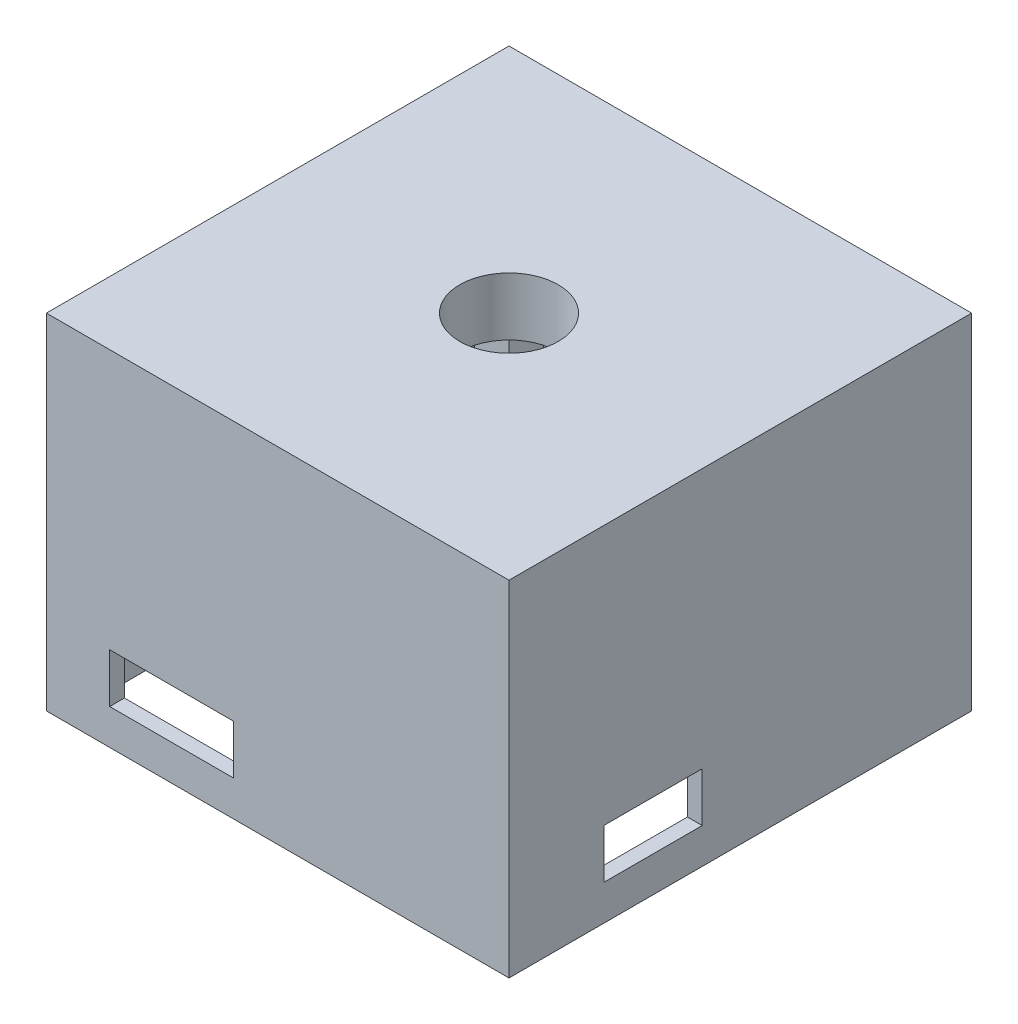
SolidWorks part; units mm, degrees
ref_plane "Front Plane" through (0, 0, 0) normal (0, 0, 1) x (1, 0, 0)
ref_plane "Top Plane" through (0, 0, 0) normal (0, 1, 0) x (1, 0, 0)
ref_plane "Right Plane" through (0, 0, 0) normal (1, 0, 0) x (0, 0, -1)
sketch "Sketch1" plane through (0, 0, 0) normal (0, 1, 0) x (1, 0, 0)
  line L1 (-23.5, -23.5) -> (23.5, -23.5)
  line L2 (-23.5, -23.5) -> (-23.5, 23.5)
  line L3 (-23.5, 23.5) -> (23.5, 23.5)
  line L4 (23.5, -23.5) -> (23.5, 23.5)
  line L5 (-23.5, -23.5) -> (23.5, 23.5) construction
  line L6 (-23.5, 23.5) -> (23.5, -23.5) construction
  point P0 (0, 0)
  dimension "D1" = 47
  dimension "D2" = 47
extrude "Boss-Extrude1" add sketch "Sketch1" along normal blind 32
sketch "Sketch2" plane through (0, 0, 0) normal (0, -1, 0) x (1, 0, 0)
  line L1 (-22, -22) -> (22, -22)
  line L2 (-22, -22) -> (-22, 22)
  line L3 (-22, 22) -> (22, 22)
  line L4 (22, -22) -> (22, 22)
  line L5 (-22, -22) -> (22, 22) construction
  line L6 (-22, 22) -> (22, -22) construction
  point P0 (0, 0)
  dimension "D1" = 44
  dimension "D2" = 44
extrude "Cut-Extrude1" cut sketch "Sketch2" against normal blind 26.1
sketch "Sketch3" plane through (0, 26.1, 0) normal (0, -1, 0) x (1, 0, 0)
  line L0 (-22, 18.5) -> (-18.5, 18.5)
  line L1 (-22, 22) -> (-18.5, 22) construction
  line L2 (-22, 22) -> (-22, 18.5) construction
  line L6 (-18.5, 18.5) -> (-18.5, 22)
  dimension "D1" = 3.5
  dimension "D2" = 3.5
extrude "Boss-Extrude2" add sketch "Sketch3" along normal blind 20.5
mirror "Mirror1" about plane through (0, 0, 0) normal (1, 0, 0) of "Boss-Extrude2" second plane through (0, 0, 0) second plane normal (0, 0, 1)
sketch "Sketch4" plane through (0, 0, -23.5) normal (0, 0, -1) x (-1, 0, 0)
  line L0 (0, 32) -> (0, 0) construction
  line L1 (-23.5, 32) -> (23.5, 32) construction
  line L121 (15, 3.1573) -> (15, 23.1573)
  line L125 (-15, 3.1573) -> (-15, 23.1573)
  line L126 (-15, 13.1573) -> (-11, 13.1573) construction
  line L132 (-13, 3.1573) -> (-11, 3.1573)
  line L135 (-13, 23.1573) -> (-11, 23.1573)
  line L136 (-13, 23.1573) -> (-13, 3.1573)
  line L137 (-13, 3.1573) -> (-11, 3.1573)
  line L138 (-11, 23.1573) -> (-11, 3.1573)
  point P5 (0, 13.1573)
  dimension "D1" = 30
  dimension "D2" = 20
extrude "Cut-Extrude3" cut sketch "Sketch4" against normal up to next contours L138 L135 L136 L132
pattern_linear "LPattern1" count 7 spacing 4 along (-1, 0, 0) of "Cut-Extrude3"
sketch "Sketch8" plane through (0, 0, -23.5) normal (0, 0, -1) x (-1, 0, 0)
  line L2 (-13, 23.1573) -> (-13, 3.1573) construction
  line L3 (-13, 21.1573) -> (13, 21.1573)
  line L4 (-13, 21.1573) -> (-13, 19.1573)
  line L6 (13, 21.1573) -> (13, 19.1573)
  line L7 (13, 23.1573) -> (13, 3.1573) construction
  line L8 (-13, 19.1573) -> (13, 19.1573)
  dimension "D1" = 2
extrude "Boss-Extrude4" add sketch "Sketch8" against normal up to vertex
pattern_linear "LPattern2" count 5 spacing 4 along (0, -1, 0) of "Boss-Extrude4"
sketch "Sketch6" plane through (0, 0, 0) normal (0, -1, 0) x (1, 0, 0)
  line L0 (-23.5, 23.5) -> (-23.5, -23.5)
  line L1 (-23.5, -23.5) -> (23.5, -23.5)
  line L2 (23.5, -23.5) -> (23.5, 23.5)
  line L3 (23.5, 23.5) -> (-23.5, 23.5)
  line L9 (-22, 22) -> (22, 22)
  line L10 (-22, 22) -> (-22, -22)
  line L11 (-22, -22) -> (22, -22)
  line L12 (22, 22) -> (22, -22)
extrude "Boss-Extrude5" add sketch "Sketch6" along normal blind 3
sketch "Sketch7" plane through (0, 32, 0) normal (0, 1, 0) x (1, 0, 0)
  circle A0 centre (0, 0) radius 5
  dimension "D1" = 10
extrude "Cut-Extrude4" cut sketch "Sketch7" against normal blind 10
sketch "Sketch9" plane through (-23.5, 0, 0) normal (-1, 0, 0) x (0, 0, 1)
sketch "Sketch10" plane through (-23.5, 0, 0) normal (-1, 0, 0) x (0, 0, 1)
  line L1 (13.8718, 0.6) -> (3.8718, 0.6)
  line L2 (13.8718, 0.6) -> (13.8718, 5.6)
  line L3 (13.8718, 5.6) -> (3.8718, 5.6)
  line L4 (3.8718, 0.6) -> (3.8718, 5.6)
  dimension "D1" = 10
  dimension "D2" = 5
extrude "Cut-Extrude5" cut sketch "Sketch10" against normal through all
sketch "Sketch12" plane through (0, 0, 23.5) normal (0, 0, 1) x (1, 0, 0)
  line L0 (-22.204, 0.6) -> (20.7721, 0.6) construction
  line L1 (-4.4975, 0.6) -> (-17.0688, 0.6)
  line L2 (-4.4975, 0.6) -> (-4.4975, 5.6)
  line L3 (-4.4975, 5.6) -> (-17.0688, 5.6)
  line L4 (-17.0688, 0.6) -> (-17.0688, 5.6)
  line L5 (-16.4228, 5.6) -> (-19.3228, 5.6) construction
extrude "Cut-Extrude6" cut sketch "Sketch12" against normal blind 10
